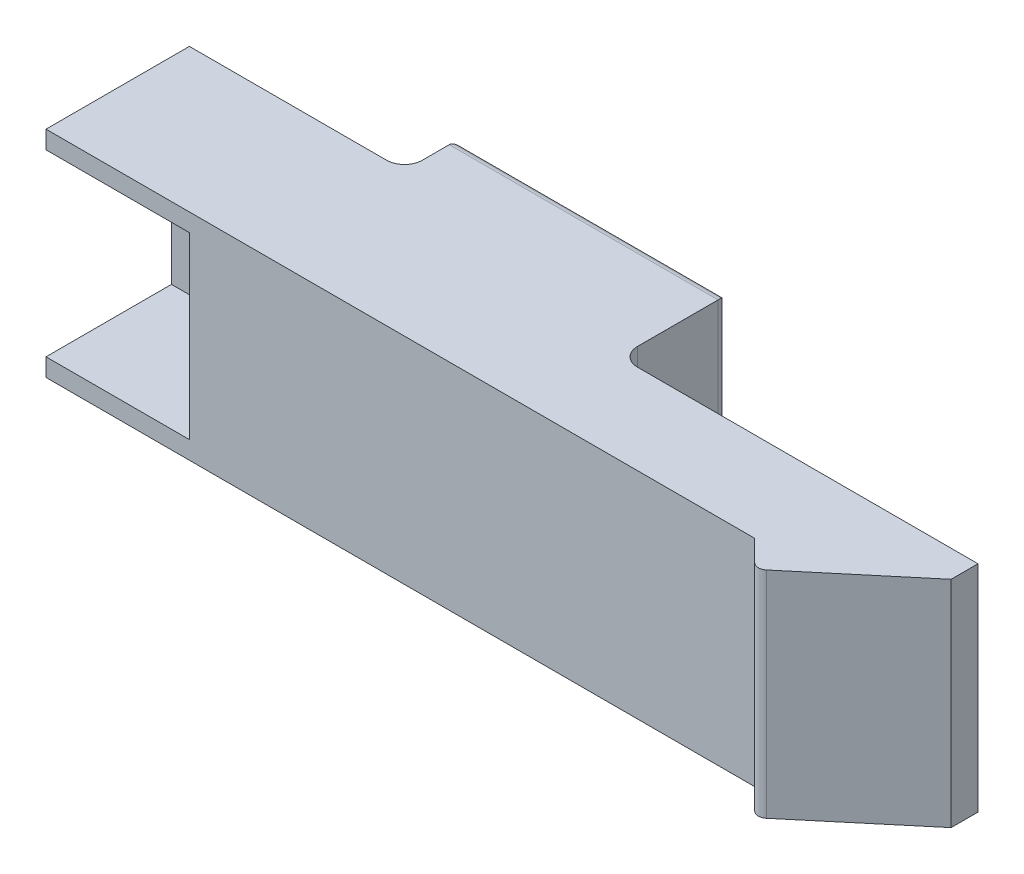
SolidWorks part; units mm, degrees
ref_plane "前视基准面" through (0, 0, 0) normal (0, 0, 1) x (1, 0, 0)
ref_plane "上视基准面" through (0, 0, 0) normal (0, 1, 0) x (1, 0, 0)
ref_plane "右视基准面" through (0, 0, 0) normal (1, 0, 0) x (0, 0, -1)
sketch "草图1" plane through (0, 0, 0) normal (0, 0, 1) x (1, 0, 0)
  line L1 (-7.5, -6) -> (7.5, -6)
  line L2 (-7.5, -6) -> (-7.5, 6)
  line L3 (-7.5, 6) -> (7.5, 6)
  line L4 (7.5, -6) -> (7.5, 6)
  line L5 (-7.5, -6) -> (7.5, 6) construction
  line L6 (-7.5, 6) -> (7.5, -6) construction
  point P0 (0, 0)
  dimension "D1" = 12
  dimension "D2" = 15
extrude "凸台-拉伸1" add sketch "草图1" along normal blind 11
shell "抽壳1" thickness 2
sketch "草图2" plane through (0, 0, 11) normal (0, 0, 1) x (1, 0, 0)
  line L0 (-7.5, 6) -> (-7.5, -6)
  line L1 (-7.5, -6) -> (-19.5, -6)
  line L2 (-19.5, -6) -> (-19.5, 6)
  line L3 (-19.5, 6) -> (-7.5, 6)
  dimension "D1" = 12
extrude "凸台-拉伸2" add sketch "草图2" against normal blind 8
sketch "草图3" plane through (-19.5, 0, 0) normal (-1, 0, 0) x (0, 0, 1)
  line L3 (11, 5) -> (11, -5)
  line L6 (11, -5) -> (4, -5)
  line L7 (4, -5) -> (4, 5)
  line L8 (4, 5) -> (11, 5)
  line L9 (11, -5) -> (4, -5)
  line L10 (4, -5) -> (4, 5)
  line L11 (4, 5) -> (11, 5)
  dimension "D1" = 1
extrude "切除-拉伸1" cut sketch "草图3" against normal blind 8
fillet "圆角1" radius 0.5 8 edges at (-5.5, 0, 0) (-7.5, 0, 0) (0, -6, 0) (0, -4, 0) (5.5, 0, 0) (7.5, 0, 0) (0, 4, 0) (0, 6, 0)
sketch "草图4" plane through (0, 0, 11) normal (0, 0, 1) x (1, 0, 0)
  line L0 (7.5, 6) -> (12.5, 6)
  line L1 (12.5, 6) -> (12.5, -6)
  line L2 (12.5, -6) -> (7.5, -6)
  line L3 (7.5, -6) -> (7.5, 6) construction
  line L4 (7.5, 6) -> (7.5, -6)
  dimension "D1" = 5
extrude "凸台-拉伸3" add sketch "草图4" against normal blind 5 contours L0 L1 L2 L4
sketch "草图5" plane through (0, 0, 0) normal (0, 1, 0) x (1, 0, 0)
  line L8 (12.5, -11) -> (-19.5, -11) construction
  line L9 (22.8, -3.7) -> (50.5926, -3.7) construction
  line L13 (12.5, -7.25) -> (35.9537, -7.25) construction
  line L14 (20.0412, -11) -> (20.0412, -6) construction
  line L15 (21.5412, -12.5) -> (27.5, -7.5)
  line L16 (27.5, -6) -> (20.0412, -6)
  line L17 (27.5, -7.5) -> (27.5, -6)
  line L18 (20.0412, -11) -> (21.5412, -12.5)
  line L19 (12.5, -11) -> (12.5, -6)
  line L20 (12.5, -6) -> (20.0412, -6)
  line L21 (12.5, -11) -> (20.0412, -11)
  line L22 (7.5, -6) -> (12.5, -6) construction
  line L23 (12.5, -6) -> (12.5, -11) construction
  dimension "D1" = 135
  dimension "D2" = 15
  dimension "D3" = 140
  dimension "D4" = 6.5
  dimension "D5" = 1.5
extrude "凸台-拉伸4" add sketch "草图5" along normal blind 6 and the other way blind 6
fillet "圆角2" radius 1 1 edges at (7.5, 0, 6)
fillet "圆角3" radius 1 1 edges at (-7.5, 0, 3)
fillet "圆角4" radius 0.5 1 edges at (21.5412, 0, 12.5)
